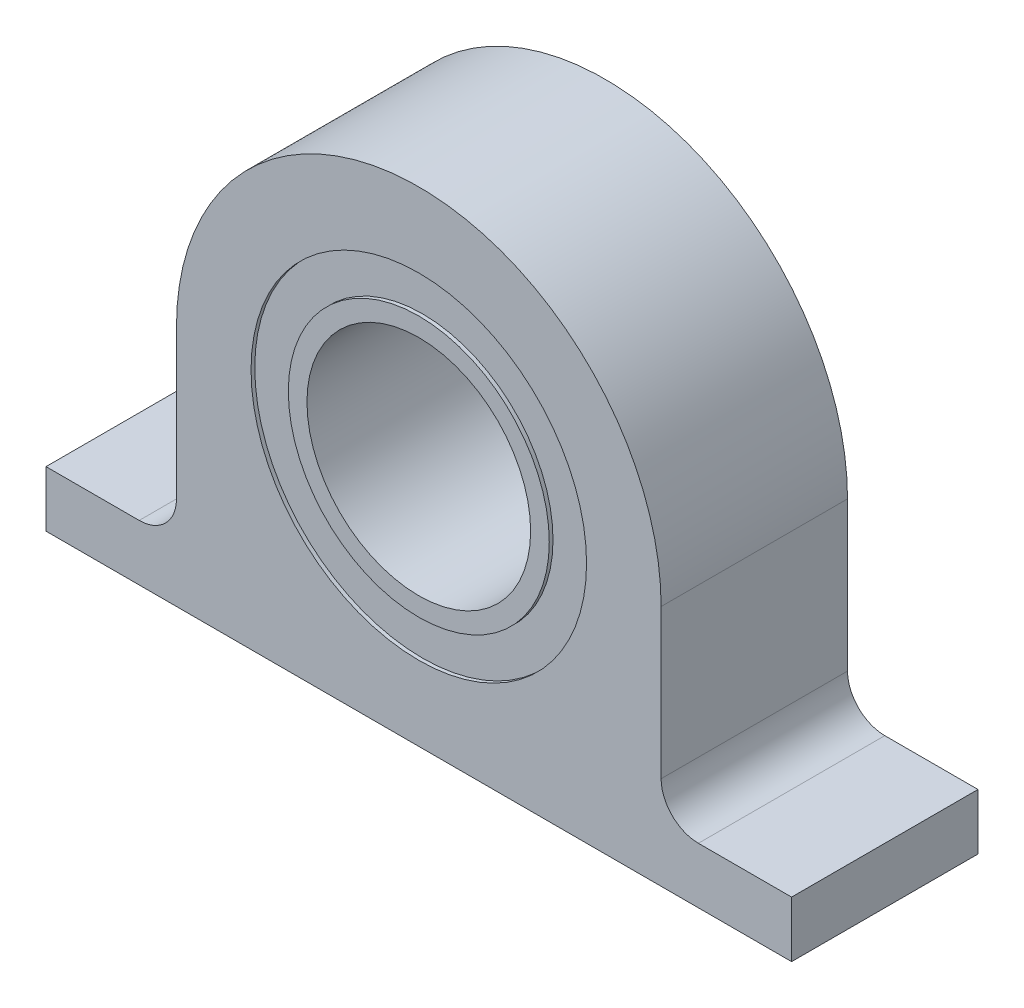
SolidWorks part; units mm, degrees
ref_plane "Front Plane" through (0, 0, 0) normal (0, 0, 1) x (1, 0, 0)
ref_plane "Top Plane" through (0, 0, 0) normal (0, 1, 0) x (1, 0, 0)
ref_plane "Right Plane" through (0, 0, 0) normal (1, 0, 0) x (0, 0, -1)
sketch "Sketch1" plane through (0, 0, 0) normal (0, 0, 1) x (1, 0, 0)
  circle A2 centre (0, 0) radius 7.62
  circle A3 centre (0, 0) radius 12.7
  dimension "D1" = 15.24
  dimension "D2" = 25.4
extrude "Boss-Extrude1" add sketch "Sketch1" along normal blind 12.7
sketch "Sketch2" plane through (0, 0, 12.7) normal (0, 0, 1) x (1, 0, 0)
  circle A0 centre (0, 0) radius 7.62 construction
  circle A1 centre (0, 0) radius 7.62
  circle A2 centre (0, 0) radius 11.43
  circle A3 centre (0, 0) radius 8.89
  dimension "D1" = 22.86
  dimension "D2" = 17.78
extrude "Cut-Extrude1" cut sketch "Sketch2" against normal blind 0.254 contours A2 A3
ref_plane "Plane1" through (0, 0, 6.35) normal (0, 0, 1) x (1, 0, 0)
mirror "Mirror1" about plane through (0, 0, 6.35) normal (0, 0, 1) of "Cut-Extrude1"
sketch "Sketch3" plane through (0, 0, 0) normal (0, 0, 1) x (1, 0, 0)
  line L0 (0, 12.7) -> (0, -12.7) construction
  line L1 (-25.4, -12.7) -> (25.4, -12.7) construction
  line L2 (-25.4, -16.51) -> (25.4, -16.51)
  line L3 (-16.51, -12.7) -> (-16.51, 0) construction
  line L4 (16.51, -12.7) -> (16.51, 0) construction
  line L5 (-25.4, -12.7) -> (-19.05, -12.7)
  line L6 (-25.4, -12.7) -> (-25.4, -16.51)
  line L7 (25.4, -12.7) -> (25.4, -16.51)
  line L8 (-16.51, 0) -> (-16.51, -10.16)
  line L10 (16.51, -10.16) -> (16.51, 0)
  line L11 (19.05, -12.7) -> (25.4, -12.7)
  circle A0 centre (0, 0) radius 12.7 construction
  arc A1 (-16.51, 0) -> (16.51, 0) centre (0, 0) cw
  arc A2 (-19.05, -12.7) -> (-16.51, -10.16) centre (-19.05, -10.16) ccw
  arc A3 (16.51, -10.16) -> (19.05, -12.7) centre (19.05, -10.16) ccw
  circle A5 centre (0, 0) radius 12.7
  point P7 (0, -12.7)
  dimension "D4" = 2.54
  dimension "D1" = 50.8
  dimension "D2" = 3.81
  dimension "D3" = 16.51
extrude "Boss-Extrude3" add sketch "Sketch3" along normal up to surface (12.7 mm away) contours L5 A2 L8 A1 L10 A3 L11 L7 L2 L6
equation "\"Shaftdia\"=0.6"
equation "\"D1@Sketch1\"=\"Shaftdia\""
equation "\"D2@Sketch1\"=\"Shaftdia\"+0.4in"
equation "\"D1@Sketch2\"=\"Shaftdia\"+0.3in"
equation "\"D2@Sketch2\"=\"Shaftdia\"+0.1"
